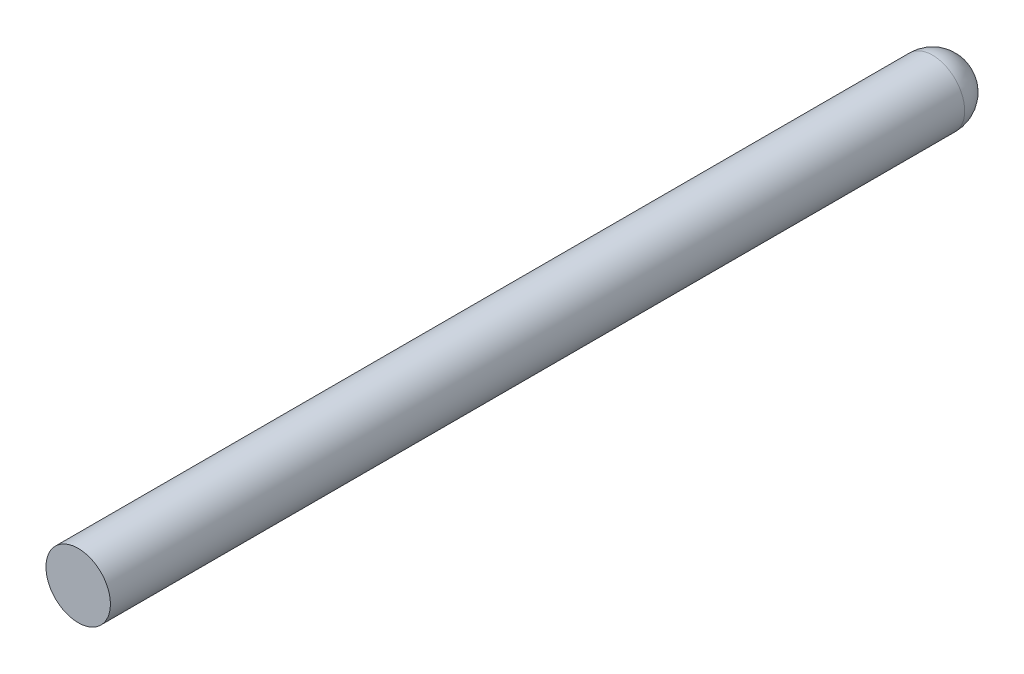
SolidWorks part; units mm, degrees
ref_plane "Front Plane" through (0, 0, 0) normal (0, 0, 1) x (1, 0, 0)
ref_plane "Top Plane" through (0, 0, 0) normal (0, 1, 0) x (1, 0, 0)
ref_plane "Right Plane" through (0, 0, 0) normal (1, 0, 0) x (0, 0, -1)
sketch "Sketch1" plane through (0, 0, 0) normal (0, 1, 0) x (1, 0, 0)
  line L0 (0, -1425.5942) -> (0, 69854.1181) construction
  line L1 (0, 0) -> (0, 110)
  line L2 (0, 0) -> (4, 0)
  line L3 (4, 0) -> (4, 106)
  arc A0 (4, 106) -> (0, 110) centre (0, 106) ccw
  point P8 (0, 0)
  dimension "D1" = 4
  dimension "D2" = 110
revolve "Revolve1" add sketch "Sketch1" angle 360 about L0
